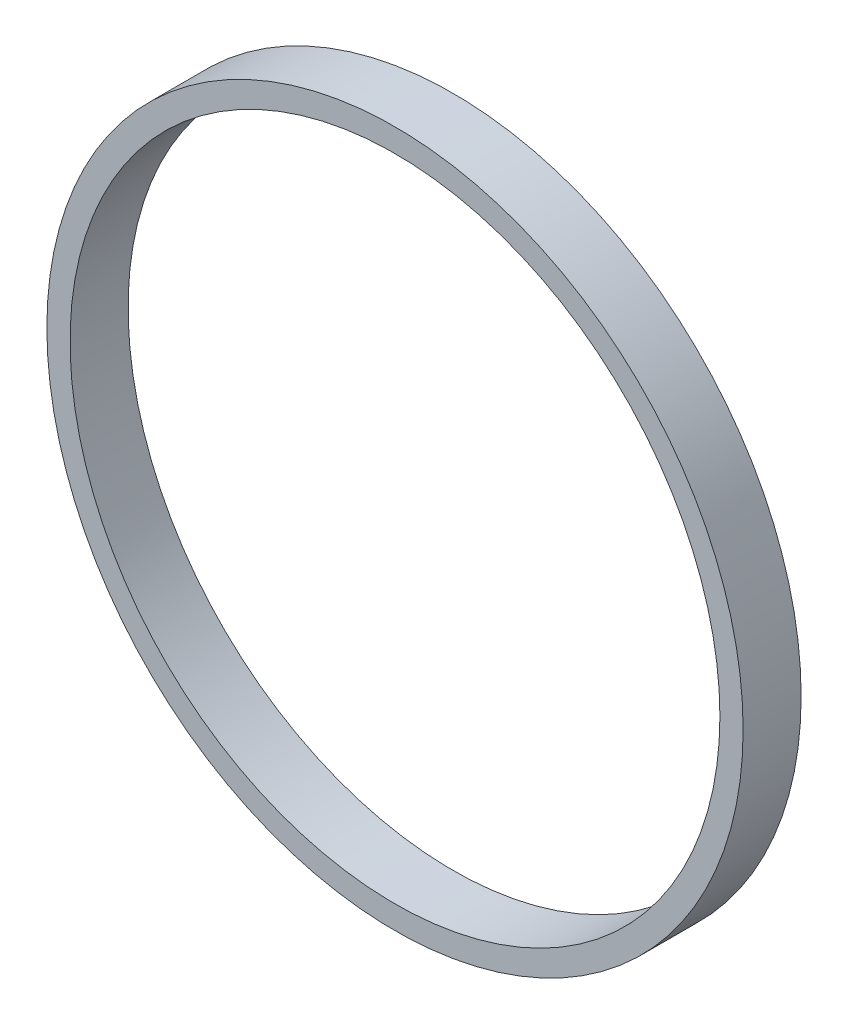
SolidWorks part; units mm, degrees
ref_plane "Front Plane" through (0, 0, 0) normal (0, 0, 1) x (1, 0, 0)
ref_plane "Top Plane" through (0, 0, 0) normal (0, 1, 0) x (1, 0, 0)
ref_plane "Right Plane" through (0, 0, 0) normal (1, 0, 0) x (0, 0, -1)
sketch "Sketch2" plane through (0, 0, 0) normal (0, 0, 1) x (1, 0, 0)
  circle A8 centre (0, 0) radius 28
  circle A9 centre (0, 0) radius 30
  point P4 (0, 0)
extrude "Boss-Extrude2" add sketch "Sketch2" along normal blind 5
